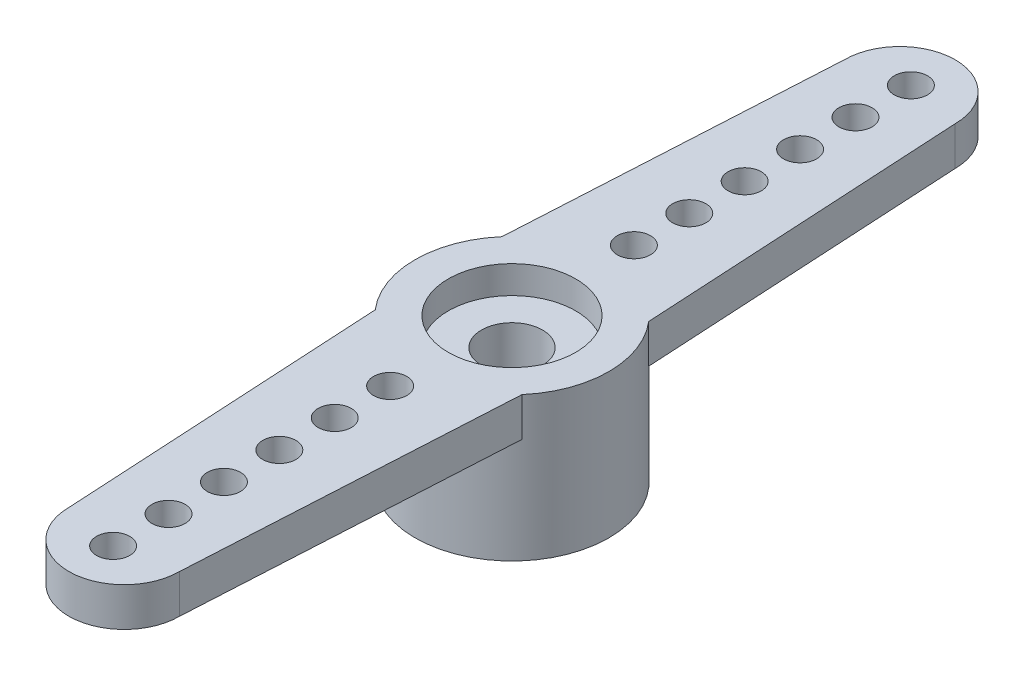
SolidWorks part; units mm, degrees
ref_plane "Front Plane" through (0, 0, 0) normal (0, 0, 1) x (1, 0, 0)
ref_plane "Top Plane" through (0, 0, 0) normal (0, 1, 0) x (1, 0, 0)
ref_plane "Right Plane" through (0, 0, 0) normal (1, 0, 0) x (0, 0, -1)
sketch "Sketch1" plane through (0, 0, 0) normal (0, 1, 0) x (1, 0, 0)
  line L0 (0, 16) -> (0, -3.5) construction
  line L1 (-3.5, 0) -> (3.5, 0) construction
  line L2 (-2, 14) -> (-2.65, 2.2864)
  line L3 (2, 14) -> (2.65, 2.2864)
  line L4 (-2, -14) -> (-2.65, -2.2864)
  line L5 (2, -14) -> (2.65, -2.2864)
  arc A0 (-2.65, 2.2864) -> (-2.65, -2.2864) centre (0, 0) ccw
  arc A1 (2, 14) -> (-2, 14) centre (0, 14) ccw
  circle A2 centre (0, 14.4) radius 0.6
  circle A3 centre (0, 12.4) radius 0.6
  circle A4 centre (0, 10.4) radius 0.6
  circle A5 centre (0, 8.4) radius 0.6
  circle A6 centre (0, 6.4) radius 0.6
  circle A7 centre (0, 4.4) radius 0.6
  circle A8 centre (0, -4.4) radius 0.6
  circle A9 centre (0, -6.4) radius 0.6
  circle A10 centre (0, -8.4) radius 0.6
  circle A11 centre (0, -10.4) radius 0.6
  circle A12 centre (0, -12.4) radius 0.6
  circle A13 centre (0, -14.4) radius 0.6
  arc A14 (2, -14) -> (-2, -14) centre (0, -14) cw
  arc A15 (2.65, 2.2864) -> (2.65, -2.2864) centre (0, 0) cw
  arc A16 (2.65, -2.2864) -> (2.65, 2.2864) centre (0, 0) ccw
  dimension "D1" = 7
  dimension "D2" = 4
  dimension "D6" = 1.2
  dimension "D3" = 14
  dimension "D4" = 5.3
  dimension "D5" = 1.6
  dimension "D7" = 6
extrude "Boss-Extrude1" add sketch "Sketch1" against normal blind 1.4 contours A15 L3 A1 L2 A0 L4 A14 L5 A12 A10 A8 A7 A6 A5 A4 A3 A2 A9 A11 A13
sketch "Sketch2" plane through (0, -1.4, 0) normal (0, -1, 0) x (-1, 0, 0)
  circle A0 centre (0, 0) radius 3.5
extrude "Boss-Extrude2" add sketch "Sketch2" along normal blind 3.8
sketch "Sketch3" plane through (0, 0, 0) normal (0, 1, 0) x (1, 0, 0)
  circle A0 centre (0, 0) radius 2.3
  dimension "D1" = 4.6
extrude "Cut-Extrude1" cut sketch "Sketch3" against normal blind 1
sketch "Sketch4" plane through (0, -5.2, 0) normal (0, -1, 0) x (-1, 0, 0)
  circle A0 centre (0, 0) radius 2.5
  dimension "D1" = 5
extrude "Cut-Extrude2" cut sketch "Sketch4" against normal blind 2
sketch "Sketch5" plane through (0, -1, 0) normal (0, 1, 0) x (1, 0, 0)
  circle A0 centre (0, 0) radius 1.1022
extrude "Cut-Extrude3" cut sketch "Sketch5" against normal up to next
